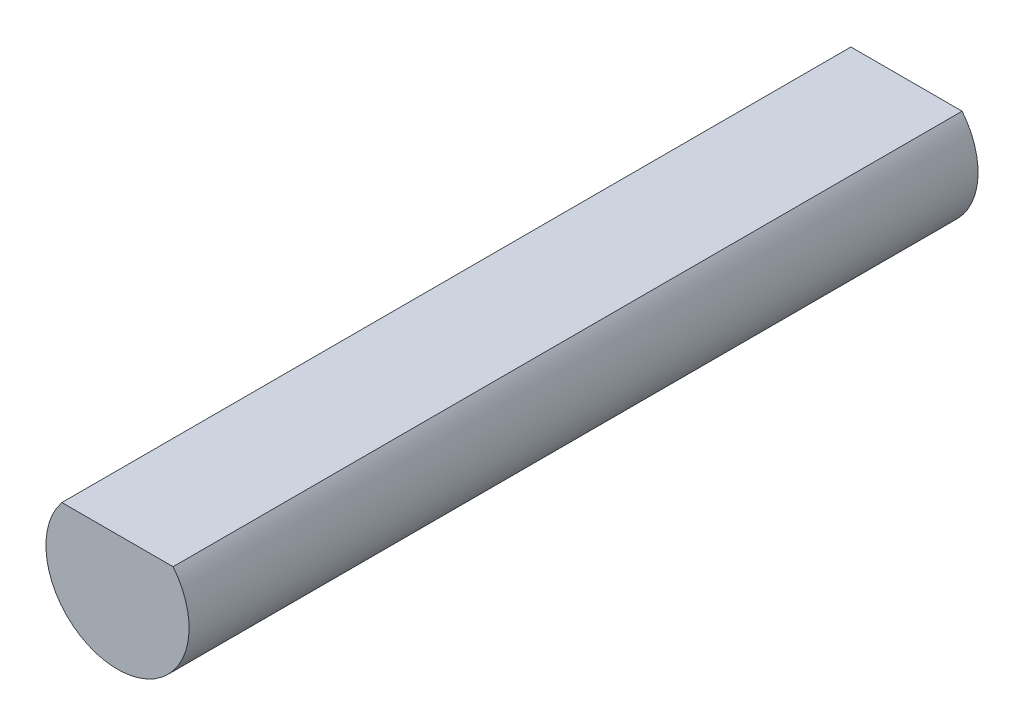
SolidWorks part; units mm, degrees
ref_plane "Front Plane" through (0, 0, 0) normal (0, 0, 1) x (1, 0, 0)
ref_plane "Top Plane" through (0, 0, 0) normal (0, 1, 0) x (1, 0, 0)
ref_plane "Right Plane" through (0, 0, 0) normal (1, 0, 0) x (0, 0, -1)
sketch "Sketch2" plane through (0, 0, 0) normal (0, 0, 1) x (1, 0, 0)
  line L0 (-2.4659, 2) -> (2.4659, 2)
  arc A0 (-2.4659, 2) -> (2.4659, 2) centre (0, 0) ccw
  dimension "D1" = 6.35
  dimension "D2" = 2
extrude "Boss-Extrude1" add sketch "Sketch2" along normal blind 35
